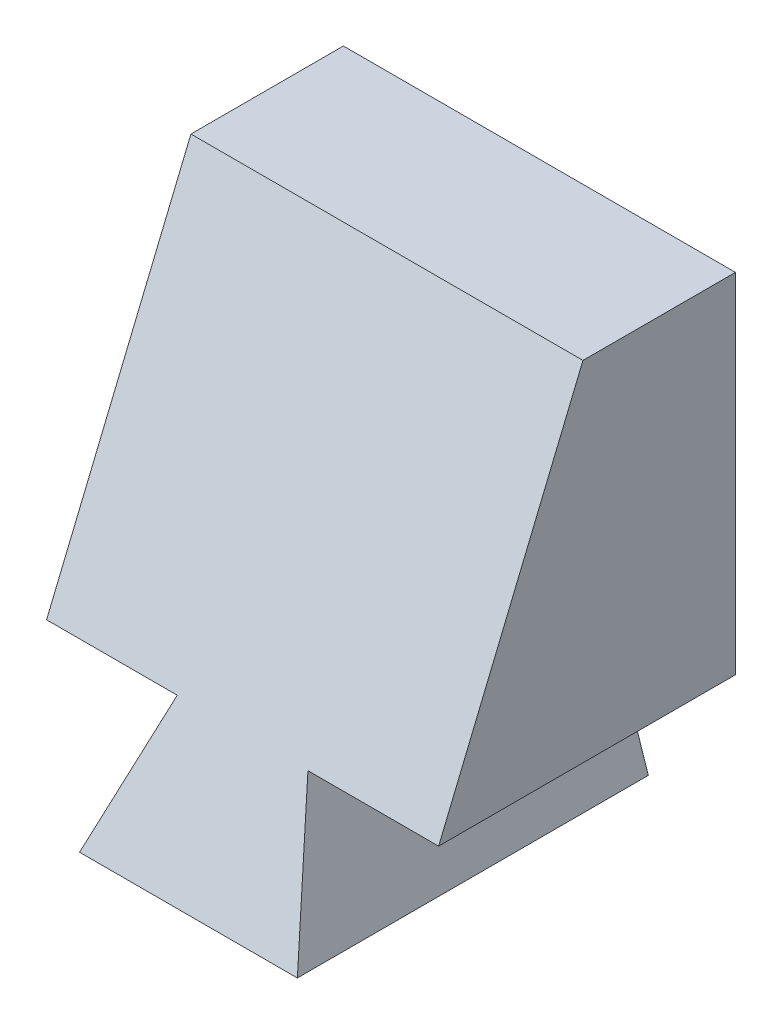
SolidWorks part; units mm, degrees
ref_plane "Front Plane" through (0, 0, 0) normal (0, 0, 1) x (1, 0, 0)
ref_plane "Top Plane" through (0, 0, 0) normal (0, 1, 0) x (1, 0, 0)
ref_plane "Right Plane" through (0, 0, 0) normal (1, 0, 0) x (0, 0, -1)
sketch "Sketch2" plane through (0, 0, 0) normal (0, 0, 1) x (1, 0, 0)
  line L4 (0.7969, 2.4048) -> (-2.2031, 2.4048)
  line L8 (-2.2031, 2.4048) -> (-2.2031, 10.4048)
  line L9 (-2.2031, 10.4048) -> (6.7969, 10.4048)
  line L10 (6.7969, 10.4048) -> (6.7969, 2.4048)
  line L11 (6.7969, 2.4048) -> (3.7969, 2.4048)
  line L12 (3.7969, 2.4048) -> (4.7969, -0.5952)
  line L13 (4.7969, -0.5952) -> (-0.2031, -0.5952)
  line L14 (-0.2031, -0.5952) -> (0.7969, 2.4048)
  dimension "D1" = 5
  dimension "D2" = 3
  dimension "D3" = 3
  dimension "D4" = 9
  dimension "D5" = 8
extrude "Boss-Extrude1" add sketch "Sketch2" along normal blind 10
sketch "Sketch3" plane through (6.7969, 0, 0) normal (1, 0, 0) x (0, 0, -1)
  line L0 (-10, 10.4048) -> (-3.5, 10.4048)
  line L2 (-10, 10.4048) -> (0, 10.4048) construction
  line L4 (-3.5, 10.4048) -> (-8.0563, -0.5952)
  line L5 (-10, -0.5952) -> (0, -0.5952) construction
  line L6 (-8.0563, -0.5952) -> (-10, -0.5952)
  line L8 (-10, -0.5952) -> (-10, 10.4048)
  line M3 (0, 10.4048) -> (-10, 10.4048)
  line M4 (-10, 10.4048) -> (-10, 2.4048)
  line M5 (-10, 2.4048) -> (0, 2.4048)
  dimension "D1" = 3.5
  dimension "D2" = 67.5
extrude "Cut-Extrude1" cut sketch "Sketch3" against normal through all both and the other way through all contours L4 M3 M4 M5 | L8 L6 L4 M5
